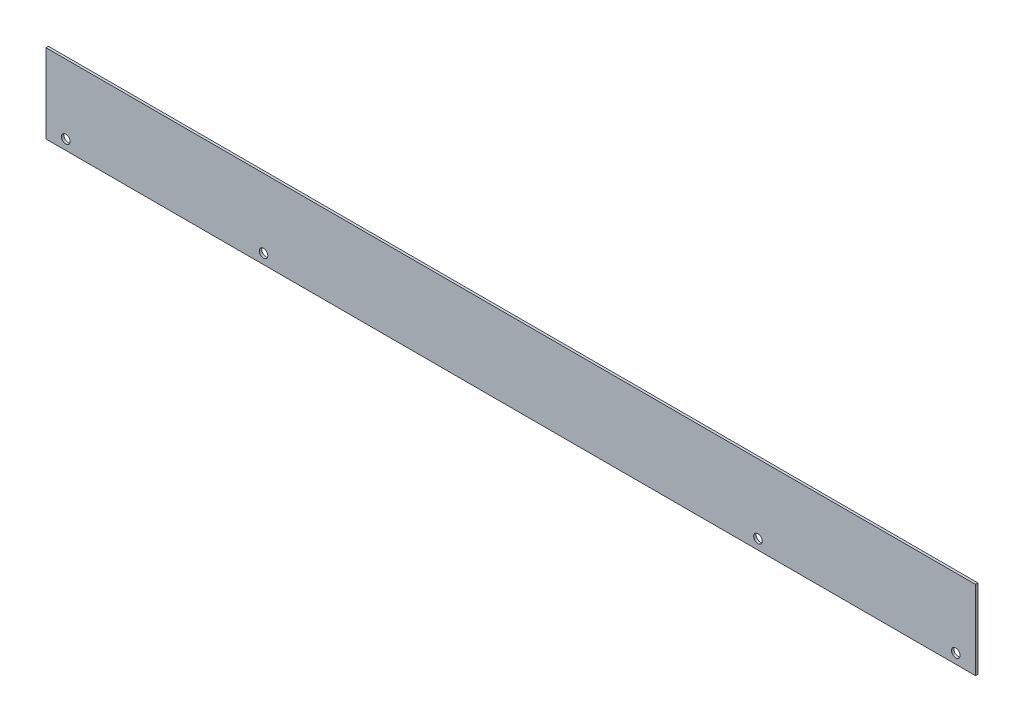
SolidWorks part; units mm, degrees
material "Acrylic (Medium-high impact)"
ref_plane "Front Plane" through (0, 0, 0) normal (0, 0, 1) x (1, 0, 0)
ref_plane "Top Plane" through (0, 0, 0) normal (0, 1, 0) x (1, 0, 0)
ref_plane "Right Plane" through (0, 0, 0) normal (1, 0, 0) x (0, 0, -1)
sketch "Sketch2" plane through (0, 0, 0) normal (0, 0, 1) x (1, 0, 0)
  line L0 (0, 0) -> (0, 50.8)
  line L1 (0, 50.8) -> (596.9, 50.8)
  line L2 (0, 0) -> (596.9, 0)
  line L3 (596.9, 0) -> (596.9, 50.8)
  dimension "D1" = 596.9
  dimension "D2" = 50.8
extrude "Boss-Extrude1" add sketch "Sketch2" along normal blind 1.5875
sketch "Sketch3" plane through (0, 0, 1.5875) normal (0, 0, 1) x (1, 0, 0)
  line L0 (0, 50.8) -> (0, 0) construction
  line L1 (596.9, 0) -> (596.9, 50.8) construction
  line L2 (0, 0) -> (596.9, 0) construction
  point P0 (12.7, 6.35)
  point P1 (139.7, 6.35)
  point P2 (457.2, 6.35)
  point P3 (584.2, 6.35)
  point P10 (0, 0)
  dimension "D1" = 127
  dimension "D2" = 127
  dimension "D3" = 12.7
  dimension "D4" = 12.7
  dimension "D5" = 6.35
  dimension "D6" = 6.35
hole_wizard "M5 Clearance Hole1" positions "Sketch4" profile "Sketch5" hole size "M5" standard "ANSI Metric" end condition through all
sketch "Sketch4" plane through (0, 0, 1.5875) normal (0, 0, 1) x (1, 0, 0)
  point P0 (584.2, 6.35)
  point P3 (457.2, 6.35)
  point P6 (139.7, 6.35)
  point P9 (12.7, 6.35)
sketch "Sketch5" plane through (584.2, 6.35, 1.5875) normal (1, 0, 0) x (0, -1, 0)
  line L0 (0, 0) -> (0, 1.5875)
  line L1 (0, 1.5875) -> (2.75, 1.5875)
  line L2 (2.75, 1.5875) -> (2.75, 0)
  line L5 (2.75, 0) -> (0, 0)
  line L11 (0, -6.35) -> (0, 107.95) construction
  dimension "Thru Hole Dia." = 5.5
  dimension "Thru Hole Depth" = 1.5875
